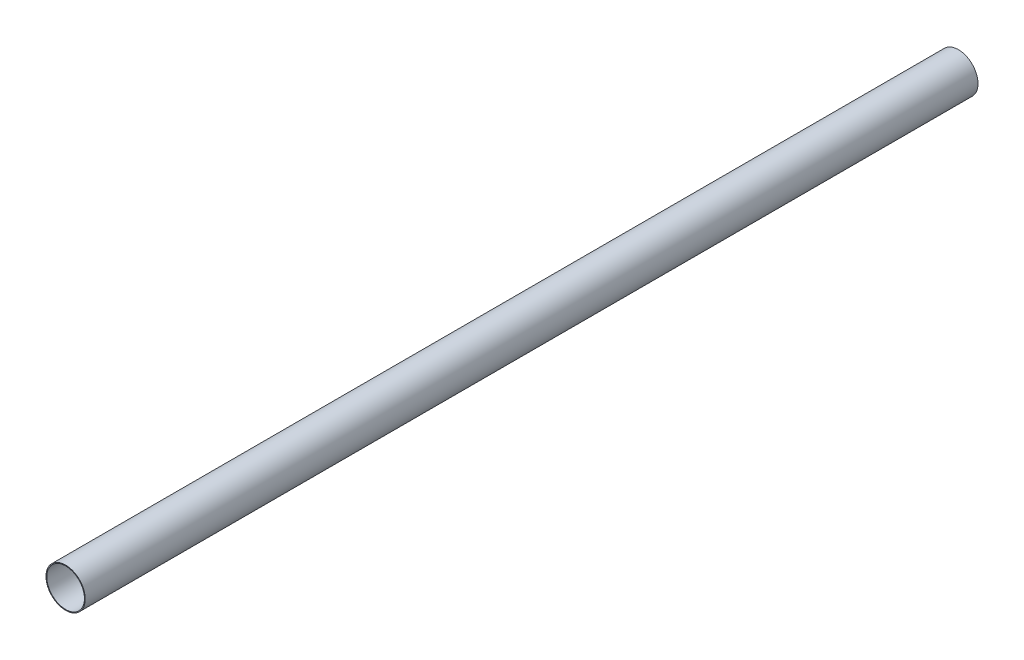
SolidWorks part; units mm, degrees
ref_plane "Front Plane" through (0, 0, 0) normal (0, 0, 1) x (1, 0, 0)
ref_plane "Top Plane" through (0, 0, 0) normal (0, 1, 0) x (1, 0, 0)
ref_plane "Right Plane" through (0, 0, 0) normal (1, 0, 0) x (0, 0, -1)
sketch "Sketch1" plane through (0, 0, 0) normal (0, 0, 1) x (1, 0, 0)
  circle A0 centre (0, 0) radius 55
  circle A1 centre (0, 0) radius 52.8
  dimension "D1" = 110
  dimension "D2" = 2.2
  dimension "D3" = 105.6
extrude "Boss-Extrude1" add sketch "Sketch1" along normal blind 2500
